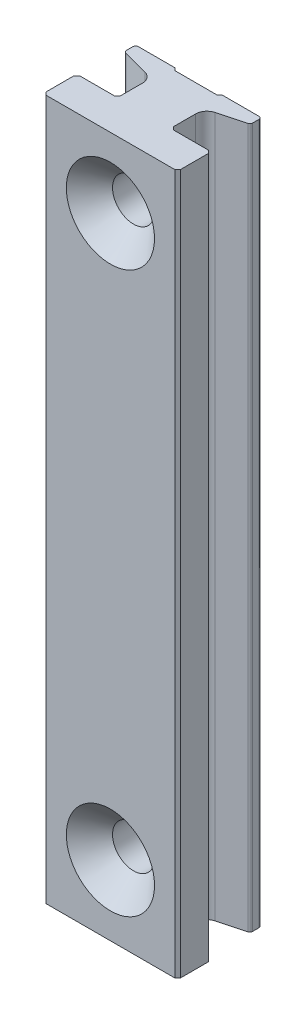
SolidWorks part; units mm, degrees
material "3.0205 (EN-AW 1200)"
ref_plane "Plan de face" through (0, 0, 0) normal (0, 0, 1) x (1, 0, 0)
ref_plane "Plan de dessus" through (0, 0, 0) normal (0, 1, 0) x (1, 0, 0)
ref_plane "Plan de droite" through (0, 0, 0) normal (1, 0, 0) x (0, 0, -1)
ref_plane "Plan1" through (0, 0, 6.3) normal (0, 0, 1) x (1, 0, 0)
sketch "Esquisse1" plane through (0, 0, 6.3) normal (0, 0, 1) x (1, 0, 0)
  line L0 (4.5, 25) -> (-4.5, 25)
  line L1 (-4.5, 25) -> (-4.5, -25)
  line L2 (-4.5, -25) -> (4.5, -25)
  line L3 (4.5, -25) -> (4.5, 25)
  line L4 (-4.5, 0) -> (4.5, 0) construction
  dimension "D1" = 9
  dimension "D2" = 50
extrude "Boss.-Extru.1" add sketch "Esquisse1" against normal blind 6.3
sketch "Esquisse2" plane through (0, 25, 0) normal (0, 1, 0) x (-1, 0, 0)
  line L0 (4.5, 6.3) -> (1.9, 6.3)
  line L1 (1.9, 6.3) -> (1.9, 0.8)
  line L2 (1.9, 0.8) -> (4.5, 0.8)
  line L3 (4.5, 0.8) -> (4.5, 6.3)
  dimension "D1" = 5.5
  dimension "D2" = 2.6
extrude "Enlèv. mat.-Extru.1" cut sketch "Esquisse2" against normal through all
sketch "Esquisse3" plane through (-1.9, 0, 0) normal (-1, 0, 0) x (0, 0, 1)
  line L0 (6.3, -25) -> (3.9, -25)
  line L1 (3.9, -25) -> (3.9, 25)
  line L2 (3.9, 25) -> (6.3, 25)
  line L3 (6.3, 25) -> (6.3, -25)
  line L4 (6.3, -25) -> (0.8, -25) construction
  dimension "D1" = 2.4
extrude "Boss.-Extru.2" add sketch "Esquisse3" along normal blind 2.9
sketch "Esquisse4" plane through (0, 25, 0) normal (0, 1, 0) x (-1, 0, 0)
  line L0 (-4.5, 1.4967) -> (-1.9, 1.4967)
  line L1 (-1.9, 1.4967) -> (-1.9, 6.3)
  line L2 (-1.9, 6.3) -> (-4.5, 6.3)
  line L3 (-4.5, 6.3) -> (-4.5, 1.4967)
  dimension "D1" = 4.8033
  dimension "D2" = 2.6
extrude "Enlèv. mat.-Extru.2" cut sketch "Esquisse4" against normal through all
sketch "Esquisse5" plane through (1.9, 0, 0) normal (1, 0, 0) x (0, 0, -1)
  line L0 (-3.9, -25) -> (-6.3, -25)
  line L1 (-6.3, -25) -> (-6.3, 25)
  line L2 (-6.3, 25) -> (-3.9, 25)
  line L3 (-3.9, 25) -> (-3.9, -25)
  line L4 (-1.4967, -25) -> (-6.3, -25) construction
  dimension "D1" = 2.4
extrude "Boss.-Extru.3" add sketch "Esquisse5" along normal blind 2.9
sketch "Esquisse6" plane through (0, -25, 0) normal (0, -1, 0) x (1, 0, 0)
  line L0 (-1.52, 0) -> (1.52, 0)
  line L1 (1.52, 0) -> (1.52, 0.18)
  line L2 (1.52, 0.18) -> (-1.52, 0.18)
  line L3 (-1.52, 0.18) -> (-1.52, 0)
extrude "Enlèv. mat.-Extru.3" cut sketch "Esquisse6" against normal through all
draft "Dépouille1" type of draft neutral plane draft angle 15 faces to draft 1 face at (-3.2, 0, 0.8) neutral plane through (-4.5, 25, 0) neutral plane normal (-1, 0, 0) parameters "D1"=15
draft "Dépouille2" type of draft neutral plane draft angle 15 faces to draft 1 face at (3.2, 0, 1.4967) neutral plane through (1.9, -25, 1.4967) neutral plane normal (1, 0, 0) parameters "D1"=15
draft "Dépouille3" type of draft neutral plane draft angle 45 faces to draft 2 face at (-1.52, 0, 0.09) face at (1.52, 0, 0.09) neutral plane through (1.52, 25, 0.18) neutral plane normal (0, 0, -1) parameters "D1"=45
hole_wizard "Fraisage pour vis à tête fraisée M31" positions "Esquisse8" profile "Esquisse7" countersink size "M3" standard "Ansi Metric" end condition through all
sketch "Esquisse8" plane through (0, 0, 6.3) normal (0, 0, 1) x (1, 0, 0)
  line L0 (0, 20) -> (0, -20) construction
  point P3 (0, 20)
  point P4 (0, -20)
  dimension "D1" = 40
sketch "Esquisse7" plane through (0, 20, 6.3) normal (1, 0, 0) x (0, -1, 0)
  line L0 (0, 0) -> (0, 6.3)
  line L1 (0, 6.3) -> (1.5, 6.3)
  line L2 (1.5, 6.3) -> (1.5, 1.65)
  line L3 (1.5, 1.65) -> (3.15, 0)
  line L5 (3.15, 0) -> (0, 0)
  line L6 (-1.5, 1.65) -> (-3.15, 0) construction
  line L11 (0, -6.35) -> (0, 107.95) construction
  dimension "Diamètre du perçage jusqu'au prochain" = 3
  dimension "Profondeur du perçage jusqu'au prochain" = 6.3
  dimension "Diamètre du fraisage entrant" = 6.3
  dimension "Angle du fraisage entrant" = 90
chamfer "Chanfrein1" distance 0.2 angle 45 6 edges at (4.8, 0, 3.9) (-4.8, 0, 3.9) (-1.9, 0, 3.9) (-4.8, 0, 6.3) (1.9, 0, 3.9) (4.8, 0, 6.3)
fillet "Congé1" radius 0.2 4 edges at (4.5, 0, 0.8) (4.5, 0, 0) (-4.5, 0, 0.8) (-4.5, 0, 0)
fillet "Congé2" radius 0.8 2 edges at (1.9, 0, 1.4967) (-1.9, 0, 1.4967)
